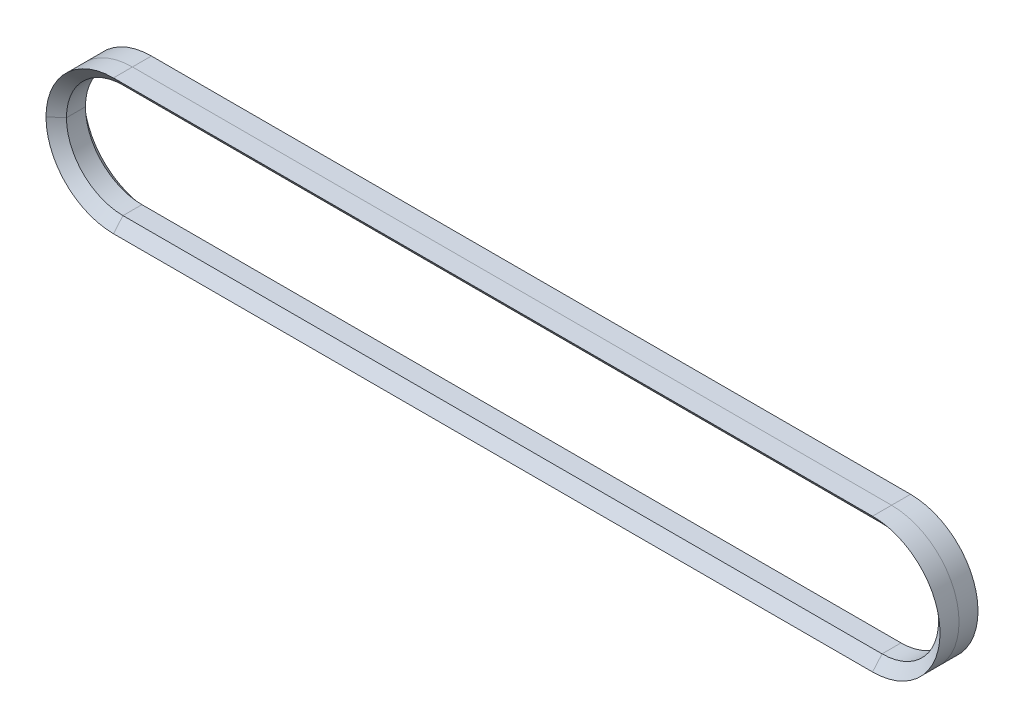
SolidWorks part; units mm, degrees
ref_plane "前视基准面" through (0, 0, 0) normal (0, 0, 1) x (1, 0, 0)
ref_plane "上视基准面" through (0, 0, 0) normal (0, 1, 0) x (1, 0, 0)
ref_plane "右视基准面" through (0, 0, 0) normal (1, 0, 0) x (0, 0, -1)
sketch "草图1" plane through (0, 0, 0) normal (0, 0, 1) x (1, 0, 0)
  line L0 (-90, 16) -> (90, 16)
  line L1 (90, -16) -> (-90, -16)
  arc A0 (-90, 16) -> (-90, -16) centre (-90, 0) ccw
  arc A1 (90, 16) -> (90, -16) centre (90, 0) cw
sketch "草图2" plane through (0, 0, 0) normal (0, 1, 0) x (1, 0, 0)
  line L0 (-106, 0) -> (-106, 4.5)
  line L1 (-106, 0) -> (-90, 0) construction
  line L2 (-106, 0) -> (-106, -4.5)
  line L3 (-103.4, 2.25) -> (-103.4, -2.25)
  line L4 (-106, 4.5) -> (-103.4, 2.25)
  line L5 (-103.4, -2.25) -> (-106, -4.5)
  dimension "D1" = 2.6
  dimension "D2" = 4.5
sweep "扫描1" add profiles "草图2" path "草图1"
